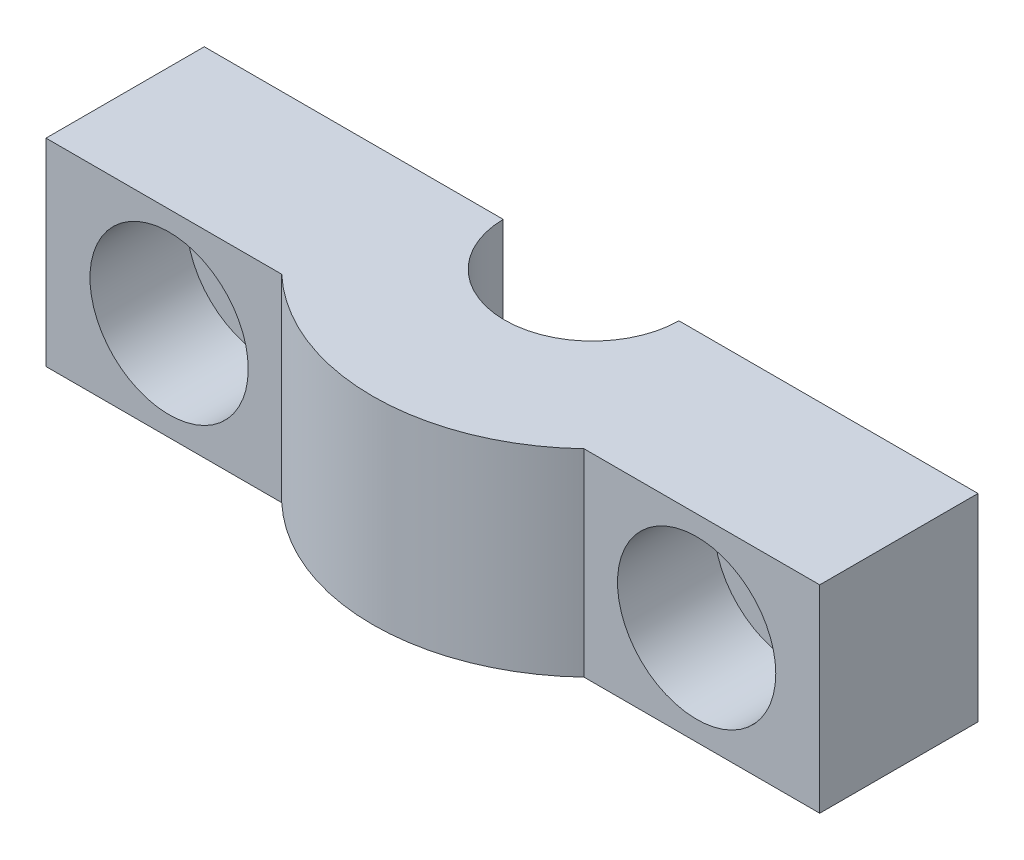
SolidWorks part; units mm, degrees
ref_plane "Front Plane" through (0, 0, 0) normal (0, 0, 1) x (1, 0, 0)
ref_plane "Top Plane" through (0, 0, 0) normal (0, 1, 0) x (1, 0, 0)
ref_plane "Right Plane" through (0, 0, 0) normal (1, 0, 0) x (0, 0, -1)
sketch "Sketch2" plane through (0, 0, 0) normal (0, 1, 0) x (1, 0, 0)
  line L0 (4.9994, -0.0762) -> (21.9999, -0.0762)
  line L1 (21.9999, -0.0762) -> (21.9999, -9.0762)
  line L2 (21.9999, -9.0762) -> (8.5949, -9.0762)
  line L3 (-4.9994, -0.0762) -> (-21.9999, -0.0762)
  line L4 (-21.9999, -0.0762) -> (-21.9999, -9.0762)
  line L5 (-21.9999, -9.0762) -> (-8.5949, -9.0762)
  arc A0 (-4.9994, -0.0762) -> (4.9994, -0.0762) centre (0, 0) ccw
  arc A1 (-8.5949, -9.0762) -> (8.5949, -9.0762) centre (0, 0) ccw
  dimension "D1" = 10
  dimension "D2" = 25
  dimension "D3" = 22
  dimension "D4" = 22
  dimension "D5" = 9
extrude "Boss-Extrude2" add sketch "Sketch2" along normal blind 11.25
sketch "Sketch3" plane through (0, 0, 9.0762) normal (0, 0, 1) x (1, 0, 0)
  line L0 (21.9999, 5.625) -> (-21.9999, 5.625) construction
  line L1 (21.9999, 11.25) -> (21.9999, 0) construction
  line L2 (-21.9999, 11.25) -> (-21.9999, 0) construction
  line L3 (8.5949, 11.25) -> (-8.5949, 11.25) construction
  line L4 (4.9994, 11.25) -> (-4.9994, 11.25) construction
  circle A0 centre (15, 5.625) radius 1.75
  circle A1 centre (-15, 5.625) radius 1.75
  point P10 (0, 11.25)
  point P13 (0, 11.25)
  dimension "D1" = 3.5
  dimension "D2" = 15
  dimension "D3" = 15
extrude "Cut-Extrude1" cut sketch "Sketch3" against normal blind 15
sketch "Sketch4" plane through (0, 0, 9.0762) normal (0, 0, 1) x (1, 0, 0)
  circle A0 centre (15, 5.625) radius 4.5
  circle A1 centre (-15, 5.625) radius 4.5
  dimension "D1" = 9
extrude "Cut-Extrude2" cut sketch "Sketch4" against normal offset from surface (5.5 mm away) 3.5 up to face at (16.75, 5.625, 0.0762)
